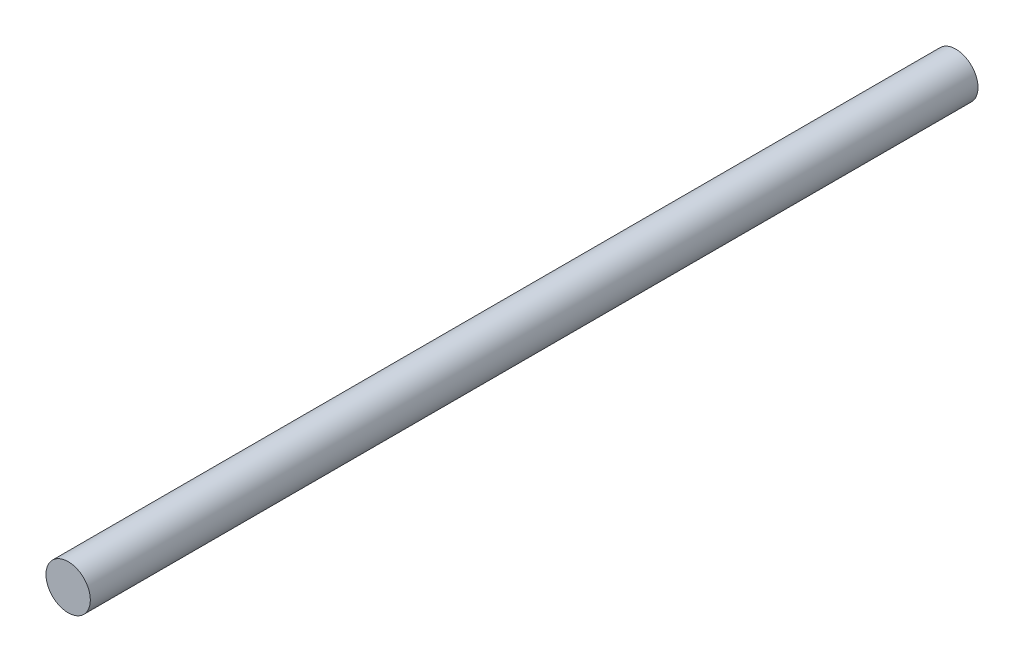
SolidWorks part; units mm, degrees
ref_plane "Front Plane" through (0, 0, 0) normal (0, 0, 1) x (1, 0, 0)
ref_plane "Top Plane" through (0, 0, 0) normal (0, 1, 0) x (1, 0, 0)
ref_plane "Right Plane" through (0, 0, 0) normal (1, 0, 0) x (0, 0, -1)
sketch "Sketch1" plane through (0, 0, 0) normal (0, 0, 1) x (1, 0, 0)
  circle A0 centre (0, 0) radius 4
  dimension "D1" = 8
extrude "Boss-Extrude1" add sketch "Sketch1" along normal mid plane 160
